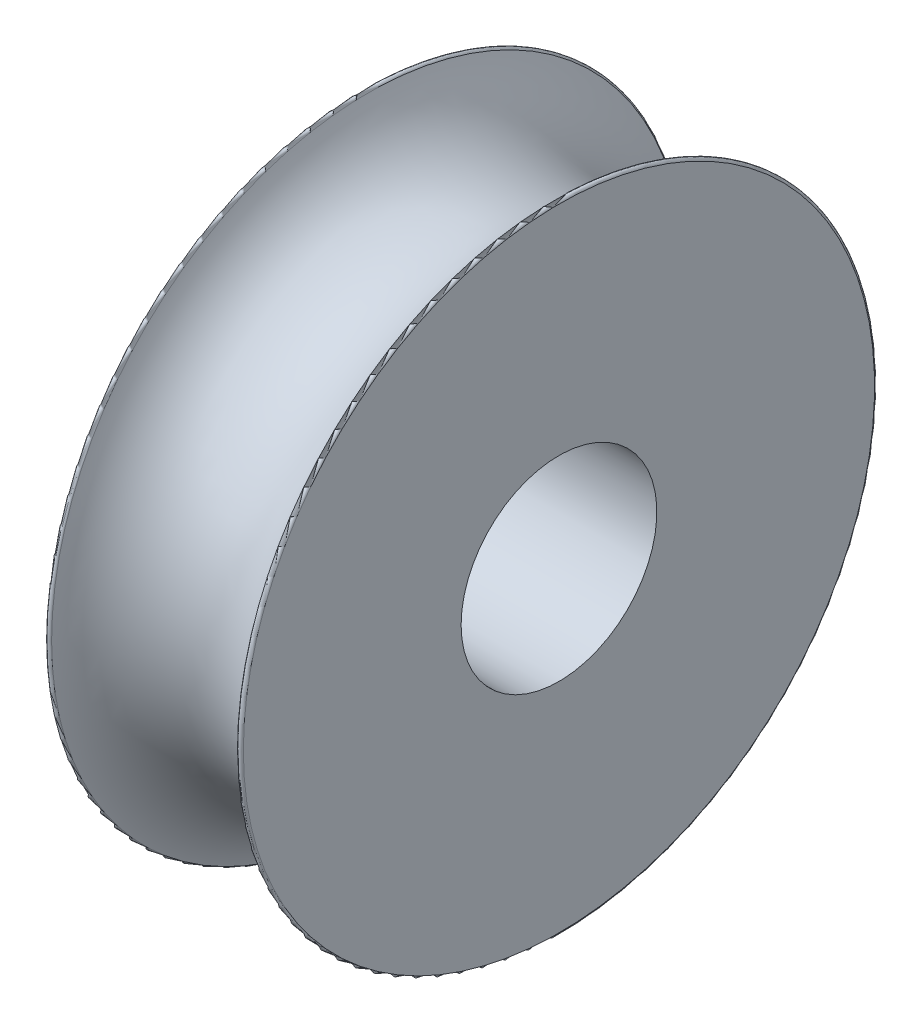
SolidWorks part; units mm, degrees
ref_plane "Front Plane" through (0, 0, 0) normal (0, 0, 1) x (1, 0, 0)
ref_plane "Top Plane" through (0, 0, 0) normal (0, 1, 0) x (1, 0, 0)
ref_plane "Right Plane" through (0, 0, 0) normal (1, 0, 0) x (0, 0, -1)
sketch "Sketch1" plane through (0, 0, 0) normal (0, 0, 1) x (1, 0, 0)
  line L0 (0, 0) -> (4, 0)
  line L1 (4, 0) -> (4, 4.4504)
  line L2 (0, 4.4504) -> (0, 0)
  line L3 (0, 0) -> (0, -2) construction
  line L4 (0, -2) -> (4, -2) construction
  line L5 (4, -2) -> (4, 0) construction
  arc A0 (3.9032, 4.4656) -> (0.0968, 4.4656) centre (2, 5.0804) cw
  arc A1 (4, 4.4504) -> (3.9032, 4.4656) centre (3.9504, 4.4504) ccw
  arc A2 (0.0968, 4.4656) -> (0, 4.4504) centre (0.0496, 4.4504) ccw
  point P10 (0.0496, 4.5)
  dimension "D1" = 0.0496
  dimension "D2" = 4
  dimension "D3" = 2
  dimension "D4" = 6.5
revolve "Revolve1" add sketch "Sketch1" angle 360 about L4
